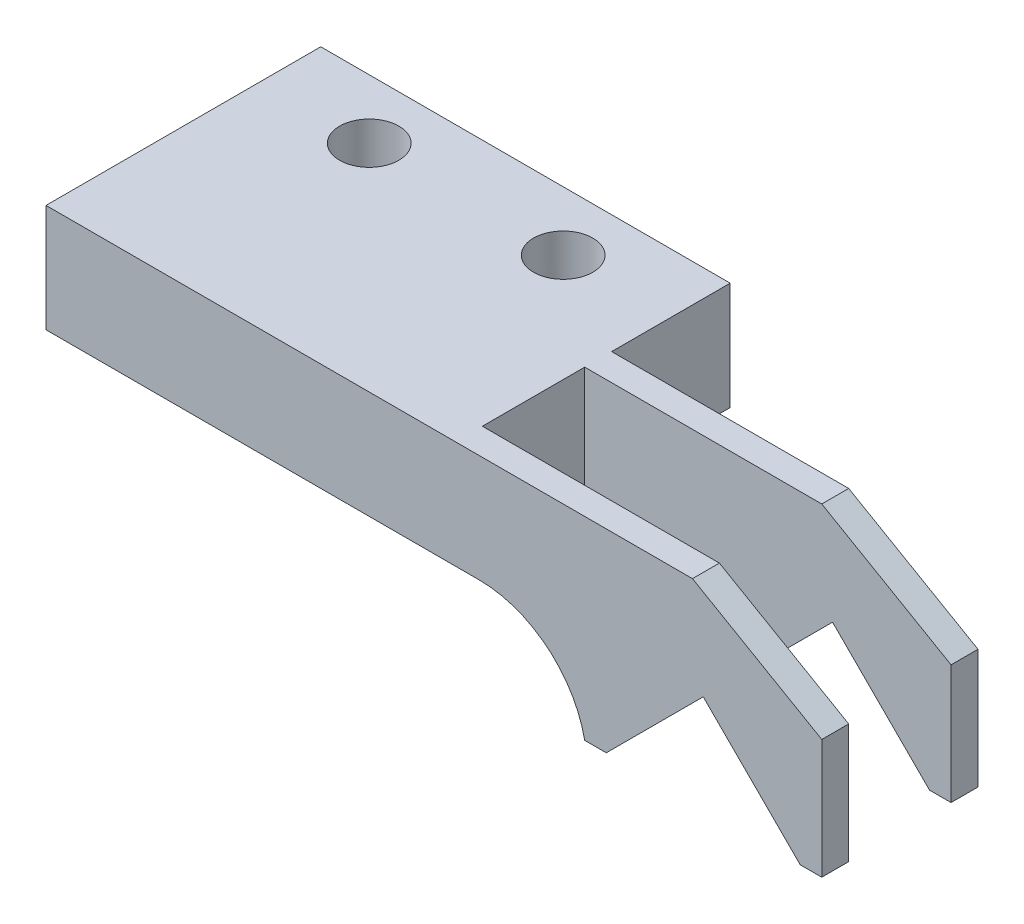
SolidWorks part; units mm, degrees
material "PW40:4:Ar:0:-1:Re:14:Ts:15:16:17:18:19:20:"
ref_plane "Plane1" through (0, 0, 0) normal (0, 0, 1) x (1, 0, 0)
ref_plane "Plane2" through (0, 0, 0) normal (0, 1, 0) x (1, 0, 0)
ref_plane "Plane3" through (0, 0, 0) normal (1, 0, 0) x (0, 0, -1)
sketch "Esquisse1" plane through (0, 0, 0) normal (0, 0, 1) x (1, 0, 0)
  line L0 (0, 0) -> (0, 10)
  line L1 (0, 10) -> (60, 10)
  line L2 (60, 10) -> (72, 3.0718)
  line L3 (72, 3.0718) -> (72, -8)
  line L4 (72, -8) -> (70, -8)
  line L5 (70, -8) -> (61, 1)
  line L6 (52, -8) -> (50, -8)
  line L8 (40.202, 0) -> (0, 0)
  line L9 (52, -8) -> (61, 1)
  arc A0 (50, -8) -> (40.202, 0) centre (40.202, -10) ccw
  dimension "D6" = 10
  dimension "D1" = 10
  dimension "D2" = 72
  dimension "D3" = 50
  dimension "D4" = 8
  dimension "D5" = 2
  dimension "D7" = 2
  dimension "D8" = 45
  dimension "D9" = 90
  dimension "D10" = 210
  dimension "D11" = 12
extrude "Base-Extrusion" add sketch "Esquisse1" along normal blind 25.5
sketch "Esquisse2" plane through (0, 10, 0) normal (0, 1, 0) x (-1, 0, 0)
  line L0 (-38, -11.3645) -> (-94.0024, -11.3645)
  line L1 (-38, -11.3645) -> (-38, 11)
  line L2 (-94.0024, 11) -> (-38, 11)
  line L3 (-94.0024, 11) -> (-94.0024, -11.3645)
  line L4 (0, 0) -> (-60, 0) construction
  line L5 (0, 25.5) -> (0, 0) construction
  dimension "D1" = 11
  dimension "D2" = 38
extrude "Enlèv. mat.-Extru.1" cut sketch "Esquisse2" against normal through all
sketch "Esquisse3" plane through (0, 10, 0) normal (0, 1, 0) x (-1, 0, 0)
  line L0 (-38, 13.5) -> (-78.9351, 13.5)
  line L1 (-38, 13.5) -> (-38, 23)
  line L2 (-78.9351, 23) -> (-38, 23)
  line L3 (-78.9351, 23) -> (-78.9351, 13.5)
  line L4 (-60, 18.25) -> (9.1753, 18.25) construction
  line L5 (-60, 25.5) -> (-60, 11) construction
  dimension "D1" = 9.5
extrude "Enlèv. mat.-Extru.2" cut sketch "Esquisse3" against normal through all
sketch "Esquisse4" plane through (0, 0, 0) normal (0, -1, 0) x (1, 0, 0)
  line L0 (38, 11) -> (38, 0) construction
  line L1 (0, 25.5) -> (0, 0) construction
  line L2 (38, 0) -> (0, 0) construction
  circle A0 centre (10, 5.5) radius 5
  circle A1 centre (28, 5.5) radius 5
  dimension "D1" = 10
  dimension "D4" = 5.5
  dimension "D6" = 10
  dimension "D2" = 10
  dimension "D3" = 10
  dimension "D5" = 5.5
extrude "Enlèv. mat.-Extru.3" cut sketch "Esquisse4" against normal blind 6
sketch "Esquisse5" plane through (0, 6, 0) normal (0, -1, 0) x (1, 0, 0)
  circle A0 centre (28, 5.5) radius 2.75
  circle A1 centre (10, 5.5) radius 2.75
  dimension "D1" = 5.5
  dimension "D2" = 5.5
extrude "Enlèv. mat.-Extru.4" cut sketch "Esquisse5" against normal blind 6
